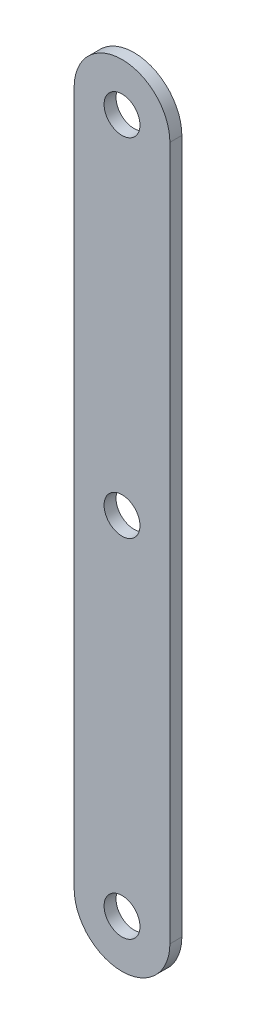
SolidWorks part; units mm, degrees
ref_plane "Front Plane" through (0, 0, 0) normal (0, 0, 1) x (1, 0, 0)
ref_plane "Top Plane" through (0, 0, 0) normal (0, 1, 0) x (1, 0, 0)
ref_plane "Right Plane" through (0, 0, 0) normal (1, 0, 0) x (0, 0, -1)
sketch "Sketch1" plane through (0, 0, 0) normal (0, 0, 1) x (1, 0, 0)
  line L0 (0, -145) -> (0, 145) construction
  line L1 (-20, -145) -> (-20, 145)
  line L2 (20, -145) -> (20, 145)
  arc A0 (-20, -145) -> (20, -145) centre (0, -145) ccw
  arc A1 (20, 145) -> (-20, 145) centre (0, 145) ccw
  circle A2 centre (0, 145) radius 7.5
  circle A3 centre (0, 0) radius 7.5
  circle A4 centre (0, -145) radius 7.5
  point P3 (0, 0)
  dimension "D1" = 20
  dimension "D3" = 15
  dimension "D4" = 15
  dimension "D5" = 15
  dimension "D6" = 0
  dimension "D2" = 290
extrude "Boss-Extrude1" add sketch "Sketch1" along normal blind 5
